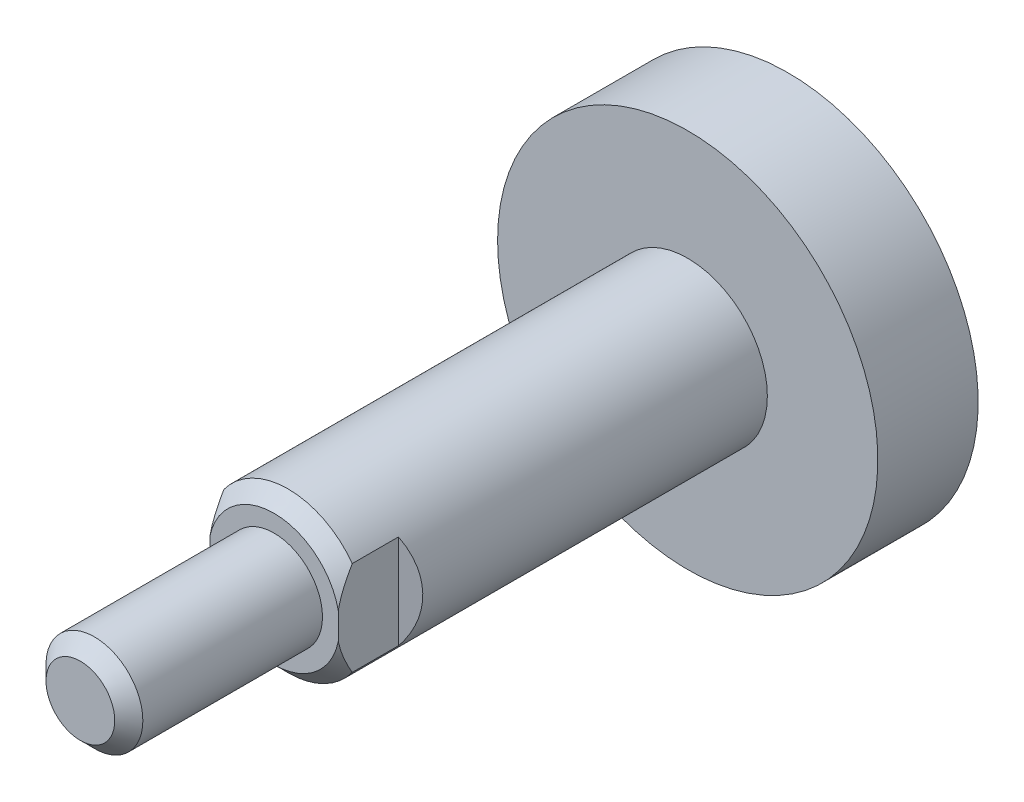
SolidWorks part; units mm, degrees
material "6061-T6 (SS)"
ref_plane "Front Plane" through (0, 0, 0) normal (0, 0, 1) x (1, 0, 0)
ref_plane "Top Plane" through (0, 0, 0) normal (0, 1, 0) x (1, 0, 0)
ref_plane "Right Plane" through (0, 0, 0) normal (1, 0, 0) x (0, 0, -1)
ref_plane "Plane1" through (0, 0, 0) normal (0, -1, 0) x (1, 0, 0)
sketch "Sketch1" plane through (0, 0, 0) normal (0, -1, 0) x (1, 0, 0)
  line L0 (9.475, 5) -> (0, 5)
  line L1 (0, 5) -> (0, 0)
  line L2 (0, 0) -> (9.475, 0)
  line L3 (9.475, 0) -> (9.475, 5)
  line L4 (0, 5) -> (0, 0) construction
revolve "Revolve1" add sketch "Sketch1" angle 360 about L4
sketch "Sketch2" plane through (0, 0, 5) normal (0, 0, 1) x (1, 0, 0)
  circle A0 centre (0, 0) radius 3.969
extrude "Boss-Extrude1" add sketch "Sketch2" along normal blind 20.614
ref_plane "Plane2" through (10.5921, 0, 18.3461) normal (-0.5, 0, -0.866) x (0, -1, 0)
sketch "Sketch4" plane through (0, 0, 25.614) normal (0, 0, 1) x (1, 0, 0)
  line L0 (3.2, 2.348) -> (3.2, -2.348)
  arc A0 (3.2, -2.348) -> (3.2, 2.348) centre (0, 0) ccw
extrude "Cut-Extrude1" cut sketch "Sketch4" against normal up to surface up to plane "Plane2"
ref_plane "Plane3" through (-10.5921, 0, 18.3461) normal (0.5, 0, -0.866) x (0, 1, 0)
sketch "Sketch6" plane through (0, 0, 25.614) normal (0, 0, 1) x (1, 0, 0)
  line L0 (-3.2, -2.348) -> (-3.2, 2.348)
  arc A0 (-3.2, 2.348) -> (-3.2, -2.348) centre (0, 0) ccw
extrude "Cut-Extrude2" cut sketch "Sketch6" against normal up to surface up to plane "Plane3"
sketch "Sketch7" plane through (0, 0, 25.614) normal (0, 0, 1) x (1, 0, 0)
  circle A0 centre (0, 0) radius 2.413
extrude "Boss-Extrude2" add sketch "Sketch7" along normal blind 9.652
chamfer "Chamfer1" distance 0.7 angle 45 3 edges at (2.413, 0, 35.266) (0, -3.969, 25.614) (0, 3.969, 25.614)
